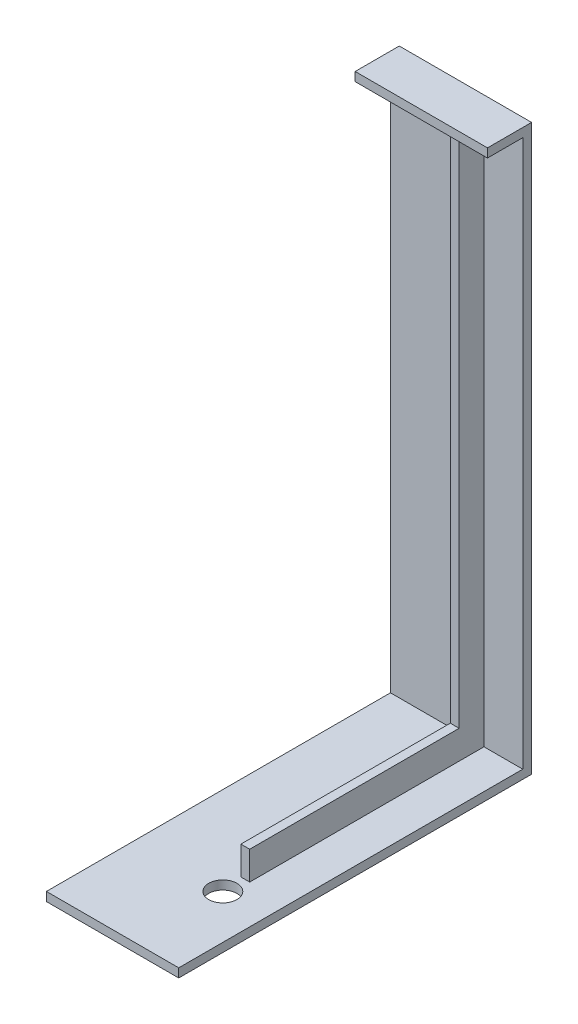
SolidWorks part; units mm, degrees
ref_plane "前视基准面" through (0, 0, 0) normal (0, 0, 1) x (1, 0, 0)
ref_plane "上视基准面" through (0, 0, 0) normal (0, 1, 0) x (1, 0, 0)
ref_plane "右视基准面" through (0, 0, 0) normal (1, 0, 0) x (0, 0, -1)
sketch "草图1" plane through (0, 0, 0) normal (0, 0, 1) x (1, 0, 0)
  line L1 (0, 0) -> (15, 0)
  line L2 (0, 0) -> (0, 64)
  line L3 (0, 64) -> (15, 64)
  line L4 (15, 0) -> (15, 64)
  dimension "D1" = 64
  dimension "D2" = 15
extrude "凸台-拉伸1" add sketch "草图1" along normal blind 40
sketch "草图2" plane through (0, 0, 40) normal (0, 0, 1) x (1, 0, 0)
  line L0 (15, 64) -> (0, 64) construction
  line L1 (-3.9484, 63) -> (26.1076, 63)
  line L2 (-3.9484, 63) -> (-3.9484, 1)
  line L3 (-3.9484, 1) -> (26.1076, 1)
  line L4 (26.1076, 63) -> (26.1076, 1)
  line L5 (0, 0) -> (15, 0) construction
  dimension "D1" = 1
  dimension "D2" = 1
extrude "切除-拉伸1" cut sketch "草图2" against normal blind 39
sketch "草图3" plane through (0, 0, 40) normal (0, 0, 1) x (1, 0, 0)
  line L1 (-3.8867, 65.4504) -> (24.6264, 65.4504)
  line L2 (-3.8867, 65.4504) -> (-3.8867, 61.8091)
  line L3 (-3.8867, 61.8091) -> (24.6264, 61.8091)
  line L4 (24.6264, 65.4504) -> (24.6264, 61.8091)
extrude "切除-拉伸2" cut sketch "草图3" against normal blind 35
sketch "草图4" plane through (0, 1, 0) normal (0, 1, 0) x (1, 0, 0)
  line L0 (15, -40) -> (0, -40) construction
  line L3 (15, -1) -> (15, -40) construction
  circle A0 centre (10, -30) radius 1.6
  point P6 (15, -26.4031)
  point P7 (15, -26.2874)
  dimension "D1" = 3.2
  dimension "D2" = 10
  dimension "D3" = 5
extrude "切除-拉伸3" cut sketch "草图4" against normal blind 35
sketch "草图5" plane through (0, 1, 0) normal (0, 1, 0) x (1, 0, 0)
  line L1 (9.6051, -0.5207) -> (10.6051, -0.5207)
  line L2 (9.6051, -0.5207) -> (9.6051, -27.5603)
  line L3 (9.6051, -27.5603) -> (10.6051, -27.5603)
  line L4 (10.6051, -0.5207) -> (10.6051, -27.5603)
  dimension "D1" = 1
extrude "凸台-拉伸2" add sketch "草图5" along normal blind 62
sketch "草图7" plane through (10.6051, 0, 0) normal (1, 0, 0) x (0, 0, -1)
  line L1 (-27.5603, 63) -> (-3.8179, 63)
  line L2 (-27.5603, 63) -> (-27.5603, 4.2276)
  line L3 (-27.5603, 4.2276) -> (-3.8179, 4.2276)
  line L4 (-3.8179, 63) -> (-3.8179, 4.2276)
extrude "切除-拉伸5" cut sketch "草图7" against normal blind 62
